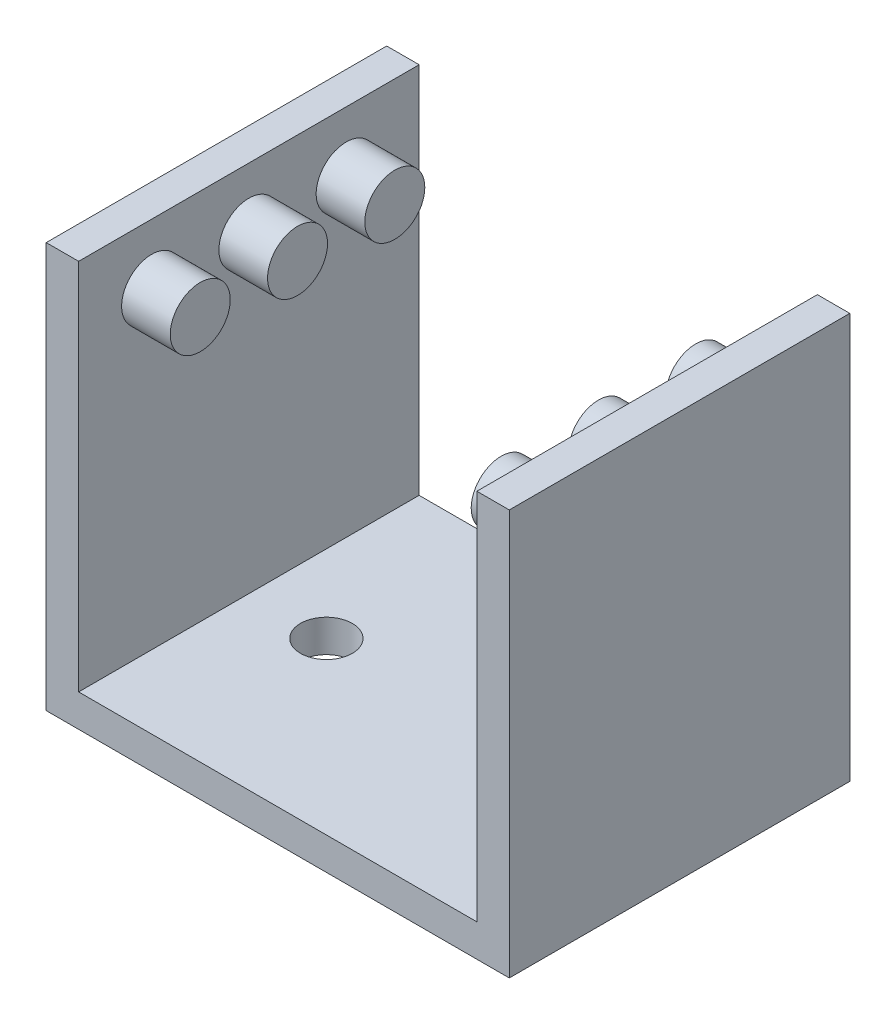
SolidWorks part; units mm, degrees
ref_plane "Front Plane" through (0, 0, 0) normal (0, 0, 1) x (1, 0, 0)
ref_plane "Top Plane" through (0, 0, 0) normal (0, 1, 0) x (1, 0, 0)
ref_plane "Right Plane" through (0, 0, 0) normal (1, 0, 0) x (0, 0, -1)
sketch "Sketch1" plane through (0, 0, 0) normal (0, 0, 1) x (1, 0, 0)
  line L2 (12.3207, -20.272) -> (14.3207, -20.272)
  line L3 (12.3207, -20.272) -> (12.3207, -43.272)
  line L5 (14.3207, -20.272) -> (14.3207, -45.272)
  line L6 (14.3207, -45.272) -> (-14.2395, -45.272)
  line L8 (12.3207, -43.272) -> (-12.2395, -43.272)
  line L11 (-14.2395, -45.272) -> (-14.2395, -20.272)
  line L12 (-14.2395, -20.272) -> (-12.2395, -20.272)
  line L13 (-12.2395, -43.272) -> (-12.2395, -20.272)
  dimension "D1" = 2
  dimension "D2" = 2
  dimension "D3" = 25
  dimension "D4" = 2
  dimension "D5" = 25
extrude "Boss-Extrude4" add sketch "Sketch1" against normal blind 21
sketch "Sketch5" plane through (-12.2395, 0, 0) normal (1, 0, 0) x (0, 0, -1)
  circle A8 centre (10.5, -24) radius 2 construction
  circle A9 centre (10.5, -24) radius 2 construction
  circle A10 centre (4.5, -24) radius 2 construction
  circle A11 centre (4.5, -24) radius 2 construction
  circle A12 centre (16.5, -24) radius 2 construction
  circle A13 centre (16.5, -24) radius 2 construction
  circle A14 centre (16.5, -24) radius 1.85
  circle A15 centre (10.5, -24) radius 1.85
  circle A16 centre (4.5, -24) radius 1.85
  dimension "D1" = 3.7
sketch "Sketch7" plane through (0, -45.272, 0) normal (0, -1, 0) x (1, 0, 0)
  line L0 (-14.2395, -10.5) -> (14.4021, -10.5) construction
  line L1 (-14.2395, -21) -> (-14.2395, 0) construction
  line L2 (14.4021, 0) -> (14.4021, -21) construction
  line L3 (0.0814, -21) -> (0, 0) construction
  circle A0 centre (-7.4593, -10.5) radius 1.6
  circle A1 centre (7.5405, -10.4418) radius 1.6
  dimension "D1" = 7.5
extrude "Cut-Extrude1" cut sketch "Sketch7" against normal blind 3
extrude "Boss-Extrude5" add sketch "Sketch5" along normal blind 3
sketch "Sketch8" plane through (12.3207, 0, 0) normal (-1, 0, 0) x (0, 0, 1)
  arc A0 (-14.5, -24) -> (-18.5, -24) centre (-16.5, -24) ccw construction
  arc A1 (-18.5, -24) -> (-14.5, -24) centre (-16.5, -24) ccw construction
  arc A2 (-14.5, -24) -> (-18.5, -24) centre (-16.5, -24) ccw construction
  arc A3 (-18.5, -24) -> (-14.5, -24) centre (-16.5, -24) ccw construction
  arc A4 (-8.5, -24) -> (-12.5, -24) centre (-10.5, -24) ccw construction
  arc A5 (-12.5, -24) -> (-8.5, -24) centre (-10.5, -24) ccw construction
  arc A6 (-8.5, -24) -> (-12.5, -24) centre (-10.5, -24) ccw construction
  arc A7 (-12.5, -24) -> (-8.5, -24) centre (-10.5, -24) ccw construction
  arc A8 (-2.5, -24) -> (-6.5, -24) centre (-4.5, -24) ccw construction
  arc A9 (-6.5, -24) -> (-2.5, -24) centre (-4.5, -24) ccw construction
  arc A10 (-2.5, -24) -> (-6.5, -24) centre (-4.5, -24) ccw construction
  arc A11 (-6.5, -24) -> (-2.5, -24) centre (-4.5, -24) ccw construction
  circle A12 centre (-16.5, -24) radius 1.85
  circle A13 centre (-10.5, -24) radius 1.85
  circle A14 centre (-4.5, -24) radius 1.85
  dimension "D1" = 3.7
extrude "Boss-Extrude6" add sketch "Sketch8" along normal blind 3
